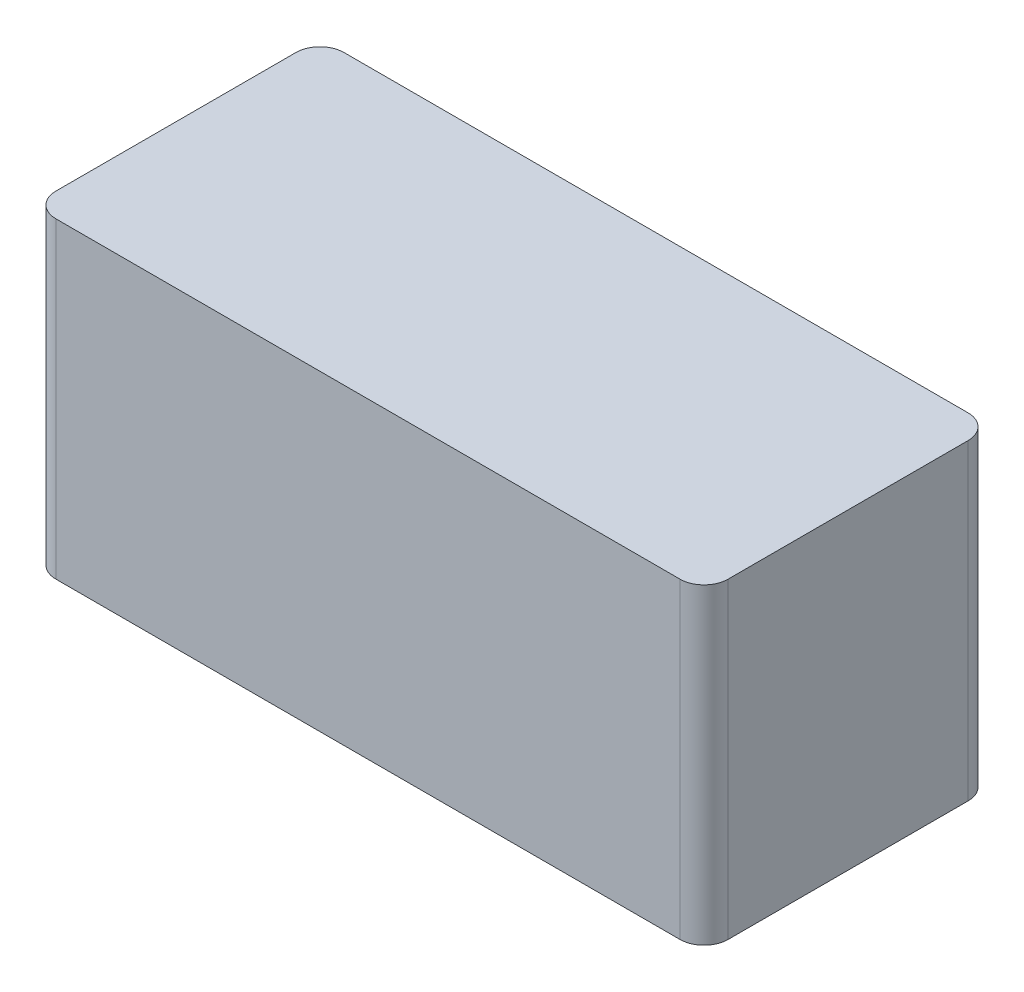
SolidWorks part; units mm, degrees
ref_plane "Front Plane" through (0, 0, 0) normal (0, 0, 1) x (1, 0, 0)
ref_plane "Top Plane" through (0, 0, 0) normal (0, 1, 0) x (1, 0, 0)
ref_plane "Right Plane" through (0, 0, 0) normal (1, 0, 0) x (0, 0, -1)
sketch "Sketch1" plane through (0, 0, 0) normal (0, 1, 0) x (1, 0, 0)
  line L1 (-70, -30) -> (70, -30)
  line L2 (-70, -30) -> (-70, 30)
  line L3 (-70, 30) -> (70, 30)
  line L4 (70, -30) -> (70, 30)
  line L5 (-70, -30) -> (70, 30) construction
  line L6 (-70, 30) -> (70, -30) construction
  point P0 (0, 0)
  dimension "D1" = 140
  dimension "D2" = 60
extrude "Boss-Extrude1" add sketch "Sketch1" along normal blind 65
fillet "Fillet1" radius 5 4 edges at (70, 32.5, 30) (70, 32.5, -30) (-70, 32.5, 30) (-70, 32.5, -30)
